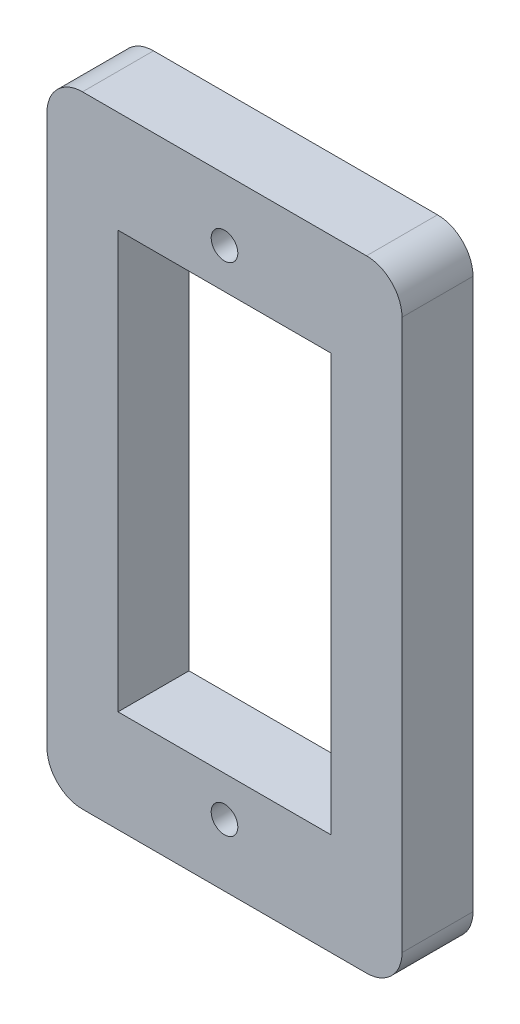
SolidWorks part; units mm, degrees
ref_plane "Ebene vorne" through (0, 0, 0) normal (0, 0, 1) x (1, 0, 0)
ref_plane "Ebene oben" through (0, 0, 0) normal (0, 1, 0) x (1, 0, 0)
ref_plane "Ebene rechts" through (0, 0, 0) normal (1, 0, 0) x (0, 0, -1)
sketch "Skizze1" plane through (0, 0, 0) normal (0, 0, 1) x (1, 0, 0)
  line L1 (-10, 17.5) -> (10, 17.5)
  line L2 (-10, 17.5) -> (-10, -17.5)
  line L3 (-10, -17.5) -> (10, -17.5)
  line L4 (10, 17.5) -> (10, -17.5)
  line L5 (-10, 17.5) -> (10, -17.5) construction
  line L6 (-10, -17.5) -> (10, 17.5) construction
  line L7 (-6, 11.75) -> (6, 11.75)
  line L8 (-6, 11.75) -> (-6, -11.75)
  line L9 (-6, -11.75) -> (6, -11.75)
  line L10 (6, 11.75) -> (6, -11.75)
  line L11 (-6, 11.75) -> (6, -11.75) construction
  line L12 (-6, -11.75) -> (6, 11.75) construction
  point P0 (0, 0)
  point P6 (0, 0)
  dimension "D1" = 23.5
  dimension "D2" = 12
  dimension "D3" = 20
  dimension "D4" = 35
extrude "Grundplatte" add sketch "Skizze1" along normal blind 4
sketch "Skizze2" plane through (0, 0, 4) normal (0, 0, 1) x (1, 0, 0)
  line L0 (0, -14) -> (0, 14) construction
  line L1 (0, 0) -> (6, 0) construction
  line L2 (6, -11.75) -> (6, 11.75) construction
  circle A0 centre (0, 14) radius 0.75
  circle A1 centre (0, -14) radius 0.75
  dimension "D1" = 1.5
  dimension "D2" = 28
extrude "Schnitt-Linear austragen1" cut sketch "Skizze2" against normal through all
fillet "Verrundung1" radius 2 4 edges at (10, -17.5, 2) (-10, -17.5, 2) (-10, 17.5, 2) (10, 17.5, 2)
